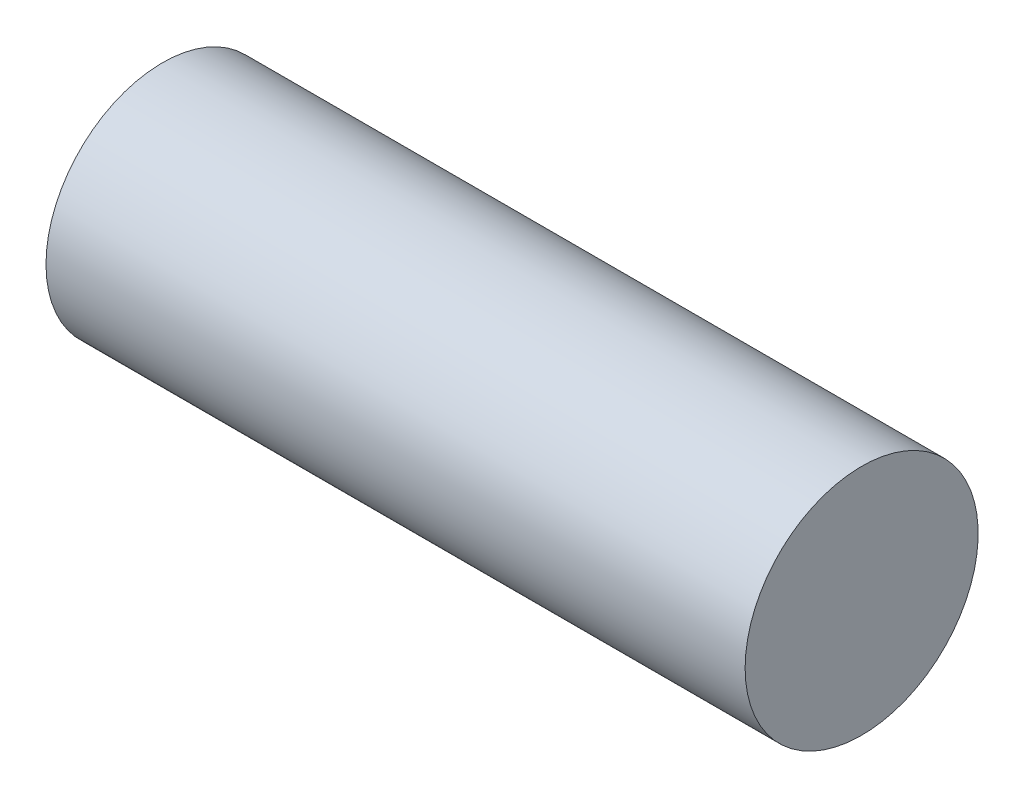
SolidWorks part; units mm, degrees
ref_plane "Ön Düzlem" through (0, 0, 0) normal (0, 0, 1) x (1, 0, 0)
ref_plane "Üst Düzlem" through (0, 0, 0) normal (0, 1, 0) x (1, 0, 0)
ref_plane "Sağ Düzlem" through (0, 0, 0) normal (1, 0, 0) x (0, 0, -1)
sketch "Sketch1" plane through (0, 0, 0) normal (0, 0, 1) x (1, 0, 0)
  line L1 (-10.2803, 7.6515) -> (19.7197, 7.6515)
  line L2 (-10.2803, 7.6515) -> (-10.2803, 2.6515)
  line L3 (-10.2803, 2.6515) -> (19.7197, 2.6515)
  line L4 (19.7197, 7.6515) -> (19.7197, 2.6515)
  dimension "D1" = 5
  dimension "D2" = 30
revolve "Revolve1" add sketch "Sketch1" angle 360 about L1
